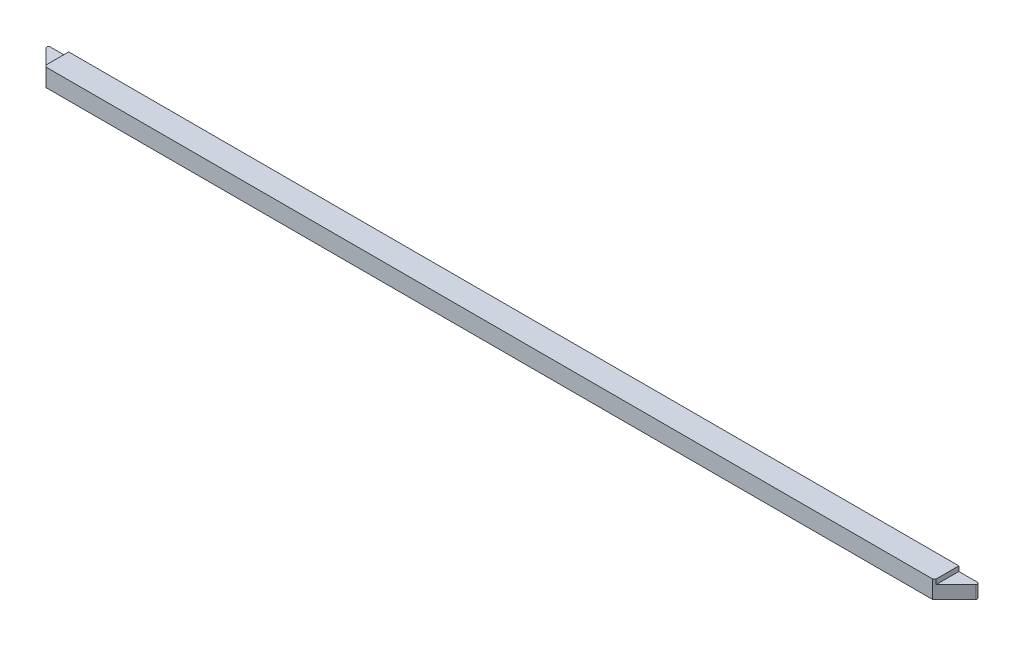
SolidWorks part; units mm, degrees
ref_plane "Plan de face" through (0, 0, 0) normal (0, 0, 1) x (1, 0, 0)
ref_plane "Plan de dessus" through (0, 0, 0) normal (0, 1, 0) x (1, 0, 0)
ref_plane "Plan de droite" through (0, 0, 0) normal (1, 0, 0) x (0, 0, -1)
sketch "Esquisse1" plane through (0, 0, 0) normal (0, 1, 0) x (1, 0, 0)
  line L7 (0, 0) -> (200, 0)
  line L8 (0, 0) -> (0, 5.5)
  line L9 (0, 5.5) -> (200, 5.5)
  line L10 (200, 0) -> (200, 5.5)
  dimension "D1" = 5.5
  dimension "D2" = 200
extrude "Boss.-Extru.1" add sketch "Esquisse1" along normal blind 4
chamfer "Chanfrein1" distance 0.4 angle 45 2 edges at (200, 2, 0) (0, 2, 0)
sketch "Esquisse2" plane through (0, 0, 0) normal (0, 1, 0) x (1, 0, 0)
  line L0 (0, 5.5) -> (-5.1, 5.5)
  line L1 (-5.1, 5.5) -> (0, 0.4)
  line L2 (0, 0.4) -> (0, 5.5)
  line L3 (0.4, 0) -> (0, 0.4) construction
extrude "Boss.-Extru.2" add sketch "Esquisse2" along normal offset from surface (2.9 mm away) 1.1 up to face at (100, 4, -1.9667)
ref_plane "Plan1" through (100, 0, 0) normal (-1, 0, 0) x (0, 0, 1)
mirror "Symétrie1" about plane through (100, 0, 0) normal (-1, 0, 0) of "Boss.-Extru.2"
fillet "Congé1" radius 0.4 2 edges at (-5.1, 1.45, -5.5) (205.1, 1.45, -5.5)
